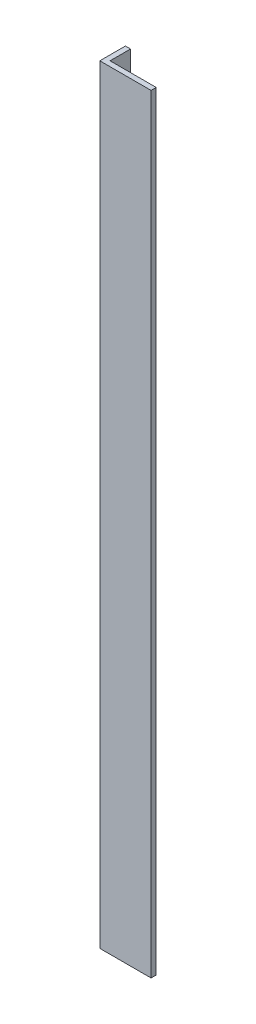
SolidWorks part; units mm, degrees
ref_plane "Front Plane" through (0, 0, 0) normal (0, 0, 1) x (1, 0, 0)
ref_plane "Top Plane" through (0, 0, 0) normal (0, 1, 0) x (1, 0, 0)
ref_plane "Right Plane" through (0, 0, 0) normal (1, 0, 0) x (0, 0, -1)
sketch "Sketch1" plane through (0, 0, 0) normal (0, 1, 0) x (1, 0, 0)
  line L0 (0, 0) -> (0, 10)
  line L1 (0, 10) -> (2, 10)
  line L2 (2, 10) -> (2, 2)
  line L3 (2, 2) -> (20, 2)
  line L4 (20, 2) -> (20, 0)
  line L5 (20, 0) -> (0, 0)
extrude "Boss-Extrude1" add sketch "Sketch1" along normal blind 300
